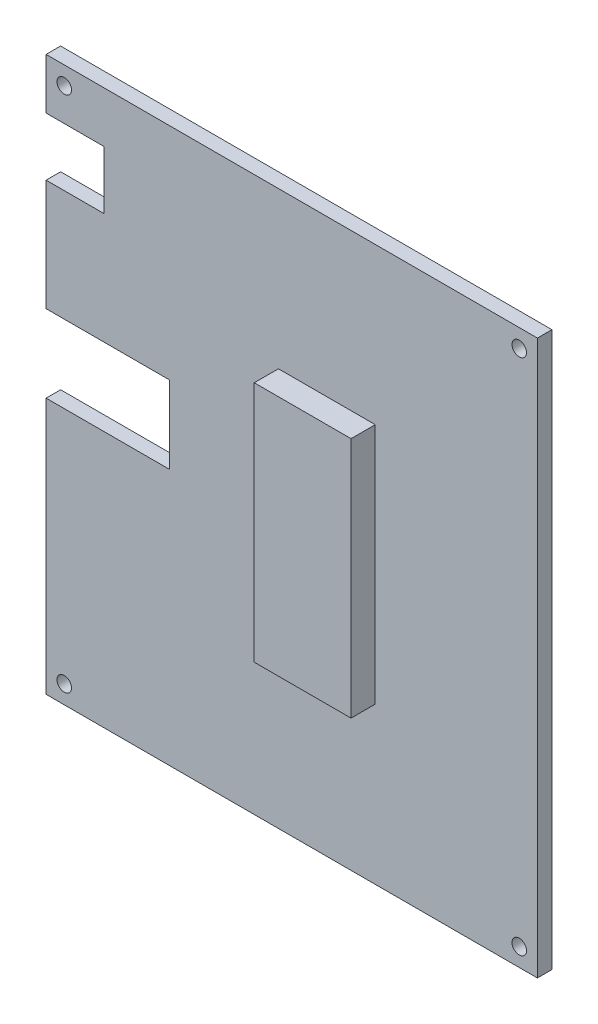
SolidWorks part; units mm, degrees
ref_plane "Front Plane" through (0, 0, 0) normal (0, 0, 1) x (1, 0, 0)
ref_plane "Top Plane" through (0, 0, 0) normal (0, 1, 0) x (1, 0, 0)
ref_plane "Right Plane" through (0, 0, 0) normal (1, 0, 0) x (0, 0, -1)
sketch "Sketch1" plane through (0, 0, 0) normal (0, 0, 1) x (-1, 0, 0)
  line L0 (50.75, 10.25) -> (50.75, 48.25)
  line L1 (-50.75, -41.25) -> (-50.75, -14.25)
  line L2 (-50.75, -14.25) -> (-50.7359, -14.3661)
  line L3 (29.75, -57.25) -> (-43.25, -57.25)
  line L4 (-43.25, -57.25) -> (-43.462, -57.4644)
  line L5 (50.75, -29.75) -> (50.75, -20.75)
  line L123 (14.75, -57.25) -> (21.75, -57.25)
  line L127 (29.75, -57.25) -> (50.75, -57.25)
  line L128 (50.75, -57.25) -> (50.75, -46.75)
  line L129 (50.75, -46.75) -> (38.75, -46.75)
  line L130 (38.75, -46.75) -> (38.75, -34.75)
  line L131 (38.75, -34.75) -> (50.75, -34.75)
  line L132 (50.75, -34.75) -> (50.75, -29.75)
  line L136 (50.75, -20.75) -> (50.75, -11.75)
  line L137 (50.75, -11.75) -> (25.25, -11.75)
  line L138 (25.25, -11.75) -> (25.25, 4.25)
  line L139 (25.25, 4.25) -> (50.75, 4.25)
  line L140 (50.75, 4.25) -> (50.75, 10.25)
  line L144 (50.75, 25.25) -> (50.75, 33.25)
  line L148 (50.75, 48.25) -> (50.75, 57.25)
  line L149 (50.75, 57.25) -> (-50.75, 57.25)
  line L150 (-50.75, 57.25) -> (-50.75, -14.25)
  line L154 (-50.75, -41.25) -> (-50.75, -57.25)
  line L155 (-50.75, -57.25) -> (-43.25, -57.25)
  line L159 (-13.25, -57.25) -> (-5.25, -57.25)
  circle A8 centre (-47, -53.5) radius 1.5
  circle A11 centre (-47, 53.5) radius 1.5
  circle A14 centre (47, 53.5) radius 1.5
  circle A17 centre (47, -53.5) radius 1.5
extrude "Boss-Extrude1" add sketch "Sketch1" along normal blind 3
sketch "Sketch2" plane through (0, 0, 0) normal (0, 0, -1) x (-1, 0, 0)
  line L1 (2.7477, -25) -> (-17.2523, -25)
  line L2 (2.7477, -25) -> (2.7477, 25)
  line L3 (2.7477, 25) -> (-17.2523, 25)
  line L4 (-17.2523, -25) -> (-17.2523, 25)
  line L5 (2.7477, -25) -> (-17.2523, 25) construction
  line L6 (0, 0) -> (-7.2523, 0) construction
  point P0 (0, 0)
  dimension "D1" = 50
  dimension "D2" = 20
extrude "Boss-Extrude2" add sketch "Sketch2" against normal blind 8
